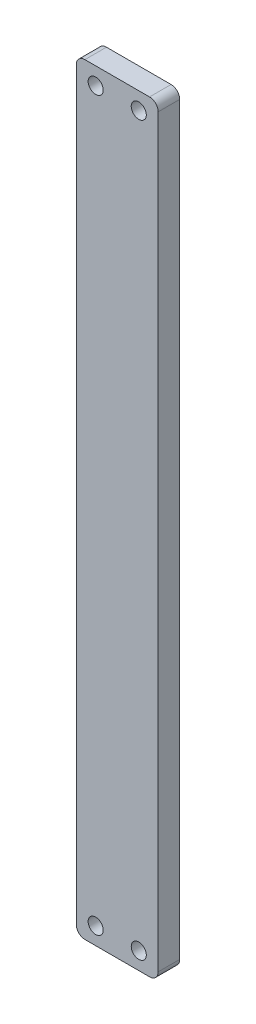
SolidWorks part; units mm, degrees
ref_plane "Front Plane" through (0, 0, 0) normal (0, 0, 1) x (1, 0, 0)
ref_plane "Top Plane" through (0, 0, 0) normal (0, 1, 0) x (1, 0, 0)
ref_plane "Right Plane" through (0, 0, 0) normal (1, 0, 0) x (0, 0, -1)
sketch "Sketch1" plane through (0, 0, 0) normal (0, 0, 1) x (1, 0, 0)
  line L2 (-9.5, -179.2703) -> (-9.5, -6.4297)
  line L3 (9.5, -179.2703) -> (9.5, -6.4297)
  line L5 (-17.4173, -92.85) -> (42.0953, -92.85) construction
  line L7 (-7.5, -4.4297) -> (7.5, -4.4297)
  line L8 (0, -15) -> (0, -13.4411) construction
  line L9 (-7.5, -181.2703) -> (7.5, -181.2703)
  circle A2 centre (5, -8.4297) radius 1.75
  circle A3 centre (-5, -8.4297) radius 1.75
  arc A4 (7.5, -4.4297) -> (9.5, -6.4297) centre (7.5, -6.4297) cw
  arc A5 (-7.5, -4.4297) -> (-9.5, -6.4297) centre (-7.5, -6.4297) ccw
  arc A6 (-7.5, -181.2703) -> (-9.5, -179.2703) centre (-7.5, -179.2703) cw
  arc A7 (7.5, -181.2703) -> (9.5, -179.2703) centre (7.5, -179.2703) ccw
  circle A8 centre (-5, -177.2703) radius 1.75
  circle A9 centre (5, -177.2703) radius 1.75
  point P15 (9.5, -4.4297)
  point P18 (-9.5, -4.4297)
  point P20 (9.5, -92.85)
  point P21 (-9.5, -92.85)
  point P29 (-9.5, -181.2703)
  point P30 (9.5, -181.2703)
  dimension "D1" = 3.5
  dimension "D2" = 3.5
  dimension "D6" = 2
  dimension "D3" = 19
  dimension "D4" = 9.5
  dimension "D5" = 4
extrude "Boss-Extrude1" add sketch "Sketch1" along normal blind 5
